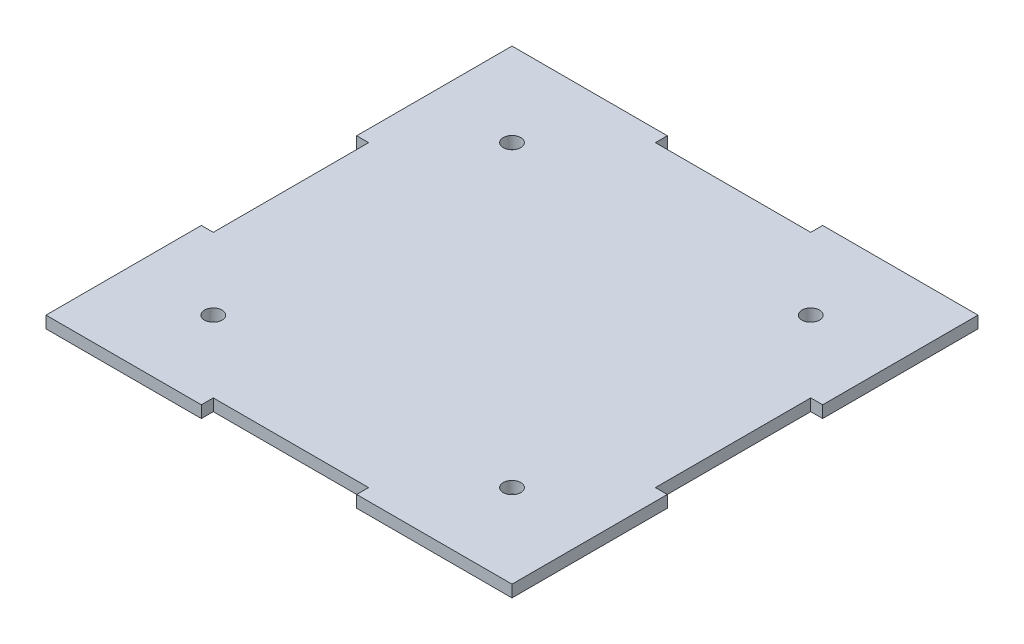
SolidWorks part; units mm, degrees
ref_plane "Front Plane" through (0, 0, 0) normal (0, 0, 1) x (1, 0, 0)
ref_plane "Top Plane" through (0, 0, 0) normal (0, 1, 0) x (1, 0, 0)
ref_plane "Right Plane" through (0, 0, 0) normal (1, 0, 0) x (0, 0, -1)
sketch "Sketch1" plane through (0, 0, 0) normal (0, 1, 0) x (1, 0, 0)
  line L0 (-58.5, 19.5) -> (-58.5, 58.5)
  line L1 (-58.5, -58.5) -> (58.5, -58.5) construction
  line L2 (-58.5, -58.5) -> (-58.5, 58.5) construction
  line L3 (-58.5, 58.5) -> (58.5, 58.5) construction
  line L4 (58.5, -58.5) -> (58.5, 58.5) construction
  line L5 (-58.5, -58.5) -> (58.5, 58.5) construction
  line L6 (-58.5, 58.5) -> (58.5, -58.5) construction
  line L7 (-55.5, -55.5) -> (55.5, -55.5) construction
  line L8 (-55.5, -55.5) -> (-55.5, 55.5) construction
  line L9 (-55.5, 55.5) -> (55.5, 55.5) construction
  line L10 (55.5, -55.5) -> (55.5, 55.5) construction
  line L11 (-55.5, -55.5) -> (55.5, 55.5) construction
  line L12 (-55.5, 55.5) -> (55.5, -55.5) construction
  line L13 (-58.5, 58.5) -> (-19.5, 58.5)
  line L14 (-19.5, 58.5) -> (-19.5, 55.5)
  line L15 (-19.5, 55.5) -> (19.5, 55.5)
  line L16 (19.5, 55.5) -> (19.5, 58.5)
  line L17 (19.5, 58.5) -> (58.5, 58.5)
  line L18 (58.5, 58.5) -> (58.5, 19.5)
  line L19 (58.5, 19.5) -> (55.5, 19.5)
  line L20 (55.5, 19.5) -> (55.5, -19.5)
  line L21 (55.5, -19.5) -> (58.5, -19.5)
  line L22 (58.5, -19.5) -> (58.5, -58.5)
  line L23 (58.5, -58.5) -> (19.5, -58.5)
  line L24 (19.5, -58.5) -> (19.5, -55.5)
  line L25 (19.5, -55.5) -> (-19.5, -55.5)
  line L26 (-19.5, -55.5) -> (-19.5, -58.5)
  line L27 (-19.5, -58.5) -> (-58.5, -58.5)
  line L28 (-58.5, -58.5) -> (-58.5, -19.5)
  line L29 (-58.5, -19.5) -> (-55.5, -19.5)
  line L30 (-55.5, -19.5) -> (-55.5, 19.5)
  line L31 (-55.5, 19.5) -> (-58.5, 19.5)
  circle A0 centre (-37.5, 37.5) radius 2.2
  circle A1 centre (37.5, 37.5) radius 2.2
  circle A2 centre (37.5, -37.5) radius 2.2
  circle A3 centre (-37.5, -37.5) radius 2.2
  point P0 (0, 0)
  point P6 (0, 0)
  point P35 (-26.586, -26.586)
  point P36 (0, 0)
  point P37 (0, 0)
  point P38 (0, 0)
  point P39 (-24.7335, -24.7335)
  dimension "D3" = 4.4
  dimension "D1" = 117
  dimension "D2" = 111
  dimension "D4" = 75
extrude "Boss-Extrude1" add sketch "Sketch1" along normal blind 3
